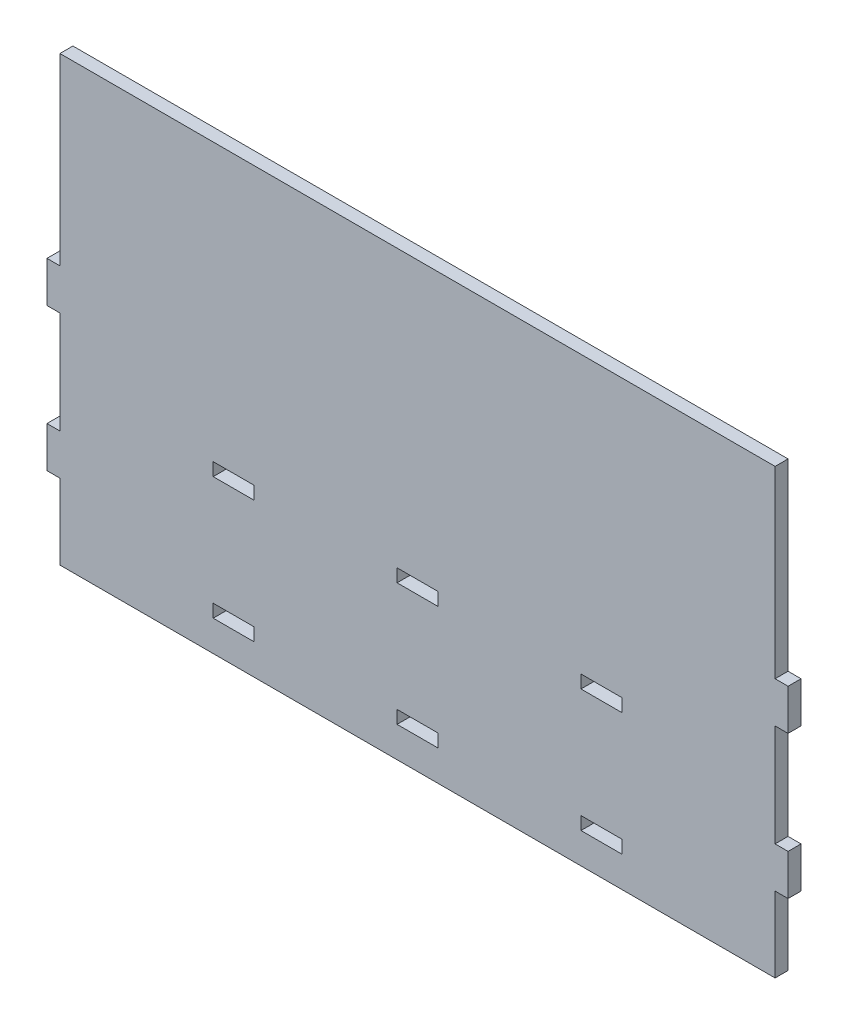
SolidWorks part; units mm, degrees
ref_plane "Alzado" through (0, 0, 0) normal (0, 0, 1) x (1, 0, 0)
ref_plane "Planta" through (0, 0, 0) normal (0, 1, 0) x (1, 0, 0)
ref_plane "Vista lateral" through (0, 0, 0) normal (1, 0, 0) x (0, 0, -1)
sketch "Croquis1" plane through (0, 0, 0) normal (0, 0, 1) x (1, 0, 0)
  line L1 (-150, -0.3673) -> (200, -0.3673)
  line L2 (-150, -0.3673) -> (-150, 201.4711)
  line L3 (-150, 201.4711) -> (200, 201.4711)
  line L4 (200, -0.3673) -> (200, 201.4711)
  dimension "D1" = 350
  dimension "D2" = 201.8383
extrude "Saliente-Extruir1" add sketch "Croquis1" along normal blind 6.35
sketch "Croquis2" plane through (-150, 0, 0) normal (-1, 0, 0) x (0, 0, 1)
  line L0 (0, 201.4711) -> (0, -0.3673) construction
  line L1 (0, 41.4727) -> (6.35, 41.4727)
  line L2 (0, 41.4727) -> (0, 21.4727)
  line L3 (0, 21.4727) -> (6.35, 21.4727)
  line L4 (6.35, 41.4727) -> (6.35, 21.4727)
  line L5 (6.35, 201.4711) -> (6.35, -0.3673) construction
  line L6 (6.35, -0.3673) -> (0, -0.3673) construction
  line L8 (6.35, 91.4727) -> (0, 91.4727)
  line L9 (6.35, 91.4727) -> (6.35, 111.4727)
  line L10 (6.35, 111.4727) -> (0, 111.4727)
  line L11 (0, 91.4727) -> (0, 111.4727)
  dimension "D1" = 21.84
  dimension "D2" = 20
  dimension "D3" = 20
  dimension "D4" = 50
extrude "Saliente-Extruir2" add sketch "Croquis2" along normal blind 6.35
ref_plane "Plano1" through (25, 0, 0) normal (1, 0, 0) x (0, 0, -1)
mirror "Simetría1" about plane through (25, 0, 0) normal (1, 0, 0) of "Saliente-Extruir2"
sketch "Croquis3" plane through (0, 0, 0) normal (0, 0, -1) x (-1, 0, 0)
  line L0 (150, -0.3673) -> (-200, -0.3673) construction
  line L1 (-35, -0.3673) -> (-15, -0.3673)
  line L2 (-35, -0.3673) -> (-35, 5.9827)
  line L3 (-35, 5.9827) -> (-15, 5.9827)
  line L4 (-15, -0.3673) -> (-15, 5.9827)
  line L25 (55, -0.3673) -> (75, -0.3673)
  line L26 (55, -0.3673) -> (55, 5.9827)
  line L27 (55, 5.9827) -> (75, 5.9827)
  line L28 (75, -0.3673) -> (75, 5.9827)
  line L29 (-125, -0.3673) -> (-105, -0.3673)
  line L30 (-125, -0.3673) -> (-125, 5.9827)
  line L31 (-125, 5.9827) -> (-105, 5.9827)
  line L32 (-105, -0.3673) -> (-105, 5.9827)
  line L33 (-35, 59.6327) -> (-15, 59.6327)
  line L34 (-35, 59.6327) -> (-35, 65.9827)
  line L35 (-35, 65.9827) -> (-15, 65.9827)
  line L36 (-15, 59.6327) -> (-15, 65.9827)
  line L37 (55, 59.6327) -> (75, 59.6327)
  line L38 (55, 59.6327) -> (55, 65.9827)
  line L39 (55, 65.9827) -> (75, 65.9827)
  line L40 (75, 59.6327) -> (75, 65.9827)
  line L41 (-125, 59.6327) -> (-105, 59.6327)
  line L42 (-125, 59.6327) -> (-125, 65.9827)
  line L43 (-125, 65.9827) -> (-105, 65.9827)
  line L44 (-105, 59.6327) -> (-105, 65.9827)
  point P6 (-25, -0.3673)
  point P7 (-25, 5.9827)
  dimension "D1" = 6.35
  dimension "D2" = 20
extrude "Cortar-Extruir1" cut sketch "Croquis3" against normal blind 6.35
sketch "Croquis4" plane through (0, 0, 6.35) normal (0, 0, 1) x (1, 0, 0)
  line L0 (200, -0.3673) -> (200, 21.4727) construction
  line L1 (-150, -0.3673) -> (200, -0.3673)
  line L2 (-150, -0.3673) -> (-150, -15.3673)
  line L3 (-150, -15.3673) -> (200, -15.3673)
  line L4 (200, -0.3673) -> (200, -15.3673)
  dimension "D1" = 15
extrude "Saliente-Extruir3" add sketch "Croquis4" against normal up to surface (6.35 mm away) up to face at (25, 46.8583, 0)
